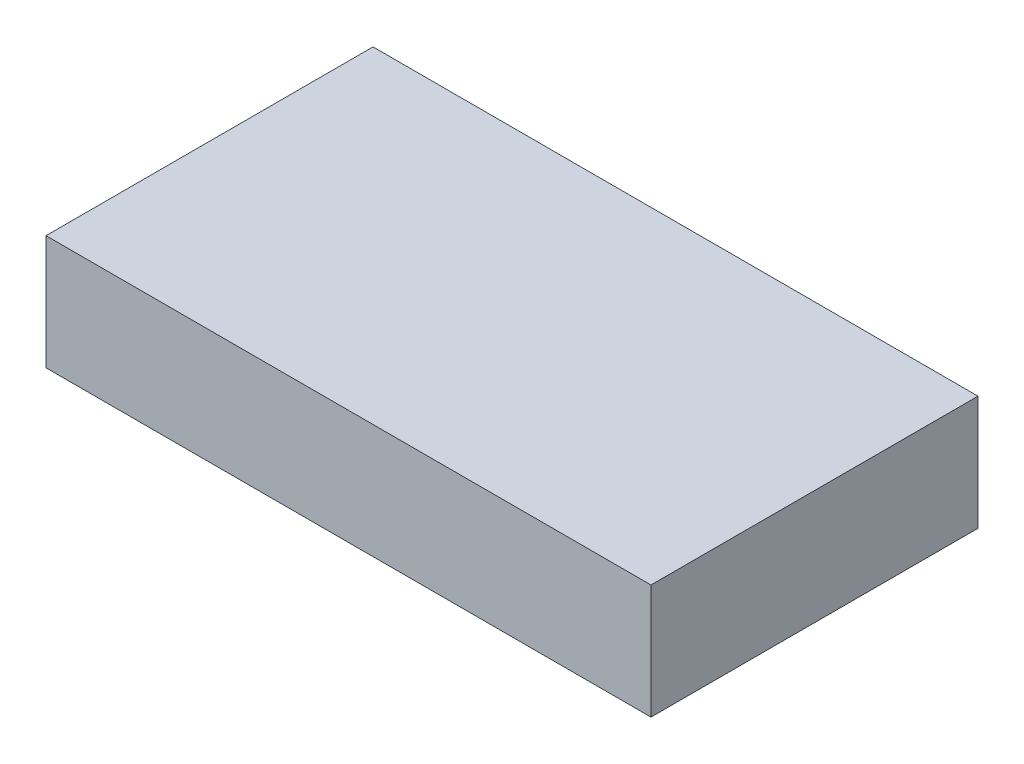
SolidWorks part; units mm, degrees
ref_plane "Front Plane" through (0, 0, 0) normal (0, 0, 1) x (1, 0, 0)
ref_plane "Top Plane" through (0, 0, 0) normal (0, 1, 0) x (1, 0, 0)
ref_plane "Right Plane" through (0, 0, 0) normal (1, 0, 0) x (0, 0, -1)
sketch "Sketch1" plane through (0, 0, 0) normal (0, 1, 0) x (1, 0, 0)
  line L0 (185, 0) -> (185, 100) construction
  line L1 (0, 0) -> (185, 0)
  line L2 (0, 0) -> (0, 100)
  line L3 (0, 100) -> (185, 100)
  line L4 (185, 0) -> (185, 100)
  line L5 (185, 100) -> (140, 100) construction
extrude "Boss-Extrude1" add sketch "Sketch1" along normal blind 35
